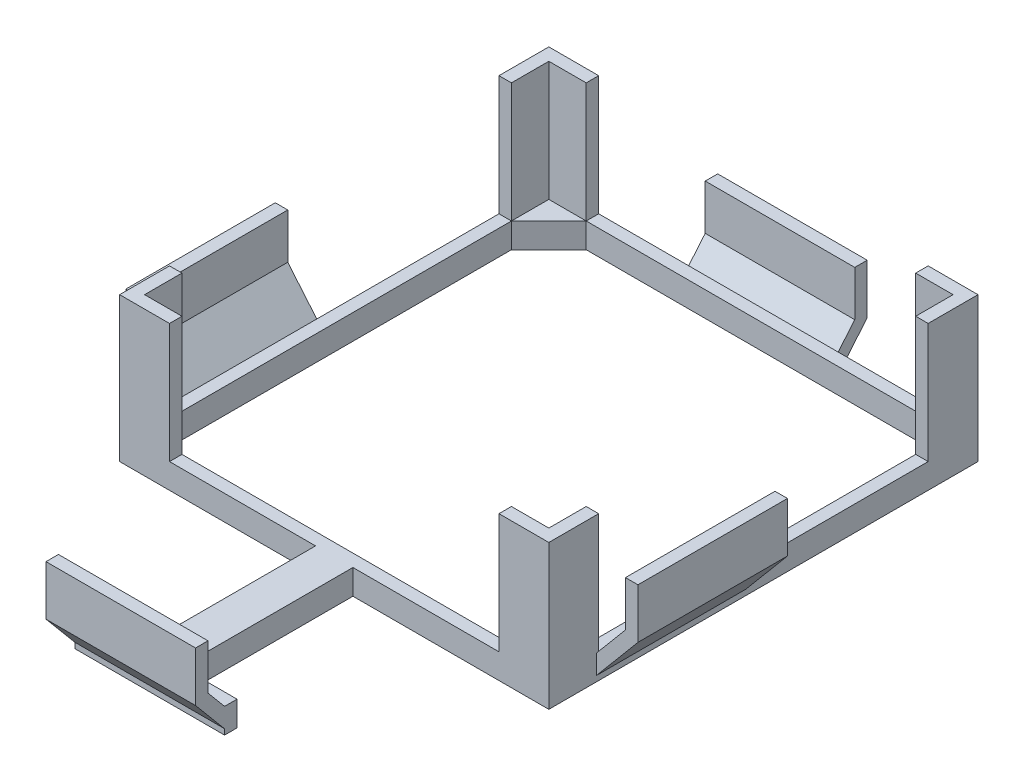
SolidWorks part; units mm, degrees
ref_plane "Front Plane" through (0, 0, 0) normal (0, 0, 1) x (1, 0, 0)
ref_plane "Top Plane" through (0, 0, 0) normal (0, 1, 0) x (1, 0, 0)
ref_plane "Right Plane" through (0, 0, 0) normal (1, 0, 0) x (0, 0, -1)
sketch "Sketch1" plane through (0, 0, 0) normal (0, 1, 0) x (1, 0, 0)
  line L0 (-81.1, 37) -> (81.1, 37) construction
  line L1 (-81.1, -44.1) -> (81.1, -44.1)
  line L2 (-81.1, -44.1) -> (-81.1, 118.1)
  line L3 (-81.1, 118.1) -> (81.1, 118.1)
  line L4 (81.1, -44.1) -> (81.1, 118.1)
  line L5 (0, 123.1) -> (0, 118.1) construction
  line L6 (-86.1, 123.1) -> (86.1, 123.1)
  line L7 (-86.1, 123.1) -> (-86.1, -49.1)
  line L8 (-86.1, -49.1) -> (86.1, -49.1)
  line L9 (86.1, 123.1) -> (86.1, -49.1)
  line L10 (0, -49.1) -> (0, -44.1) construction
  line L11 (-81.1, 37) -> (-86.1, 37) construction
  line L12 (81.1, 37) -> (86.1, 37) construction
  point P4 (0, 118.1)
  dimension "D1" = 162.2
  dimension "D2" = 162.2
  dimension "D3" = 37
  dimension "D4" = 5
extrude "base" add sketch "Sketch1" against normal blind 10
chamfer "ledges" distance 15 angle 45 4 edges at (-81.1, -5, 44.1) (81.1, -5, 44.1) (81.1, -5, -118.1) (-81.1, -5, -118.1)
sketch "Sketch2" plane through (0, 0, 0) normal (0, 1, 0) x (1, 0, 0)
  line L0 (-81.1, 103.1) -> (-86.1, 103.1)
  line L1 (-81.1, 103.1) -> (-81.1, -29.1) construction
  line L2 (-86.1, 123.1) -> (-86.1, -49.1) construction
  line L3 (-86.1, 103.1) -> (-86.1, 123.1)
  line L4 (-86.1, 123.1) -> (-66.1, 123.1)
  line L5 (86.1, 123.1) -> (-86.1, 123.1) construction
  line L6 (-66.1, 123.1) -> (-66.1, 118.1)
  line L7 (66.1, 118.1) -> (-66.1, 118.1) construction
  line L8 (-66.1, 118.1) -> (-81.1, 118.1)
  line L9 (-81.1, 118.1) -> (-81.1, 103.1)
extrude "post" add sketch "Sketch2" along normal blind 48
ref_plane "Front-centered" through (0, 0, -37) normal (0, 0, 1) x (1, 0, 0)
mirror "mirrored-posts" about plane through (0, 0, -37) normal (0, 0, 1) of "post" second plane through (0, 0, 0) second plane normal (1, 0, 0)
sketch "Sketch7" plane through (0, 0, 0) normal (0, 0, 1) x (1, 0, 0)
  line L0 (86.1, -7.7786) -> (102.75, 12.0641)
  line L1 (102.75, 12.0641) -> (102.75, 32.0641)
  line L2 (102.75, 32.0641) -> (97.75, 32.0641)
  line L3 (97.75, 32.0641) -> (97.75, 13.8839)
  line L4 (97.75, 13.8839) -> (86.1, 0)
  line L5 (86.1, -10) -> (86.1, 48) construction
  line L6 (86.1, 0) -> (86.1, -7.7786)
  line L7 (97.75, 13.8839) -> (101.5802, 10.67) construction
  line L8 (-86.1, -10) -> (86.1, -10) construction
  dimension "D4" = 5
  dimension "D1" = 50
  dimension "D2" = 20
  dimension "D3" = 102.75
extrude "side-arm" add sketch "Sketch7" along normal mid plane 60
mirror "side-arm-mirrored" about plane through (0, 0, 0) normal (1, 0, 0) of "side-arm"
sketch "Sketch8" plane through (0, 0, 0) normal (1, 0, 0) x (0, 0, -1)
  line L0 (123.1, -7.7786) -> (134.75, 6.1053)
  line L1 (123.1, -10) -> (123.1, 48) construction
  line L2 (134.75, 6.1053) -> (134.75, 26.1053)
  line L3 (134.75, 26.1053) -> (129.75, 26.1053)
  line L4 (129.75, 26.1053) -> (129.75, 7.9252)
  line L5 (129.75, 7.9252) -> (123.1, 0)
  line L6 (123.1, 0) -> (123.1, -7.7786)
  line L7 (-49.1, -10) -> (-123.1, -10)
  line L8 (-123.1, -7.7786) -> (-134.75, 6.1053)
  line L9 (-134.75, 6.1053) -> (-134.75, 26.1053)
  line L10 (-134.75, 26.1053) -> (-129.75, 26.1053)
  line L11 (-129.75, 26.1053) -> (-129.75, 7.9252)
  line L12 (-129.75, 7.9252) -> (-123.1, 0)
  line L13 (-123.1, 0) -> (-49.1, 0)
  line L14 (-49.1, -10) -> (-49.1, 48) construction
  line L15 (-49.1, 0) -> (-49.1, -10)
  line L16 (129.75, 7.9252) -> (133.5802, 4.7112) construction
  line L17 (-129.75, 7.9252) -> (-133.5802, 4.7112) construction
  line L18 (-134.75, 26.1053) -> (134.75, 26.1053) construction
  line L20 (123.1, -7.7786) -> (134.75, -7.7786) construction
  line L21 (134.75, -7.7786) -> (134.75, 6.1053) construction
  line L22 (-123.1, -10) -> (-123.1, -7.7786)
  point P14 (0, 26.1053)
  dimension "D1" = 5
  dimension "D2" = 269.5
  dimension "D3" = 50
  dimension "D4" = 50
  dimension "D5" = 20
extrude "top-bottom-arms" add sketch "Sketch8" along normal mid plane 60
sketch "Sketch9" plane through (0, 0, 0) normal (0, 1, 0) x (1, 0, 0)
  line L0 (30, -49.1) -> (66.1, -49.1) construction
  line L1 (-30, -49.1) -> (-7.5, -49.1)
  line L2 (-30, -49.1) -> (-30, -118.1)
  line L3 (-30, -118.1) -> (-7.5, -118.1)
  line L4 (-7.5, -49.1) -> (-7.5, -118.1)
  line L5 (30, -49.1) -> (7.5, -49.1)
  line L6 (30, -49.1) -> (30, -118.1)
  line L7 (30, -118.1) -> (7.5, -118.1)
  line L8 (7.5, -49.1) -> (7.5, -118.1)
  line L9 (30, -49.1) -> (30, -123.1) construction
  line L10 (30, -123.1) -> (-30, -123.1) construction
  dimension "D1" = 15
  dimension "D2" = 5
extrude "bottom-arm-cutout" cut sketch "Sketch9" against normal through all
equation "\"box_length\"= 269.5mm"
equation "\"box_width\"= 205.5mm"
equation "\"base_height\"= 10mm"
equation "\"wall_height\"= 20mm"
equation "\"offset_SI\"= 37mm"
equation "\"D1@Sketch1\" = \"Lx@block<1>.Part\" + \"tolerance\""
equation "\"D2@Sketch1\" = \"Ly@block<1>.Part\" + \"tolerance\""
equation "\"D3@Sketch1\"=\"offset_SI\""
equation "\"thick\"= 5mm"
equation "\"D4@Sketch1\" = \"thick\""
equation "\"D1@post\" = \"Lz@block<1>.Part\" * 2"
equation "\"D1@base\" = \"base_height\""
equation "\"brace_width\"= 15mm"
equation "\"D1@ledges\" = \"brace_width\""
equation "\"D1\"= \"base_height\""
equation "\"wall_width\"= 60mm"
equation "\"angle\"= 50"
equation "\"tolerance\"= 0.2mm"
equation "\"D2@Sketch7\"=\"wall_height\""
equation "\"D1@Sketch7\"=\"angle\""
equation "\"D3@Sketch7\"=\"box_width\"/2"
equation "\"D1@side-arm\" = \"wall_width\""
equation "\"D4@Sketch7\"=\"thick\""
equation "\"D1@Sketch8\"=\"thick\""
equation "\"D2@Sketch8\"=\"box_length\""
equation "\"D3@Sketch8\"=\"angle\""
equation "\"D4@Sketch8\"=\"angle\""
equation "\"D5@Sketch8\"=\"wall_height\""
equation "\"D1@top-bottom-arms\" = \"wall_width\""
equation "\"D2@Sketch9\"=\"thick\""
